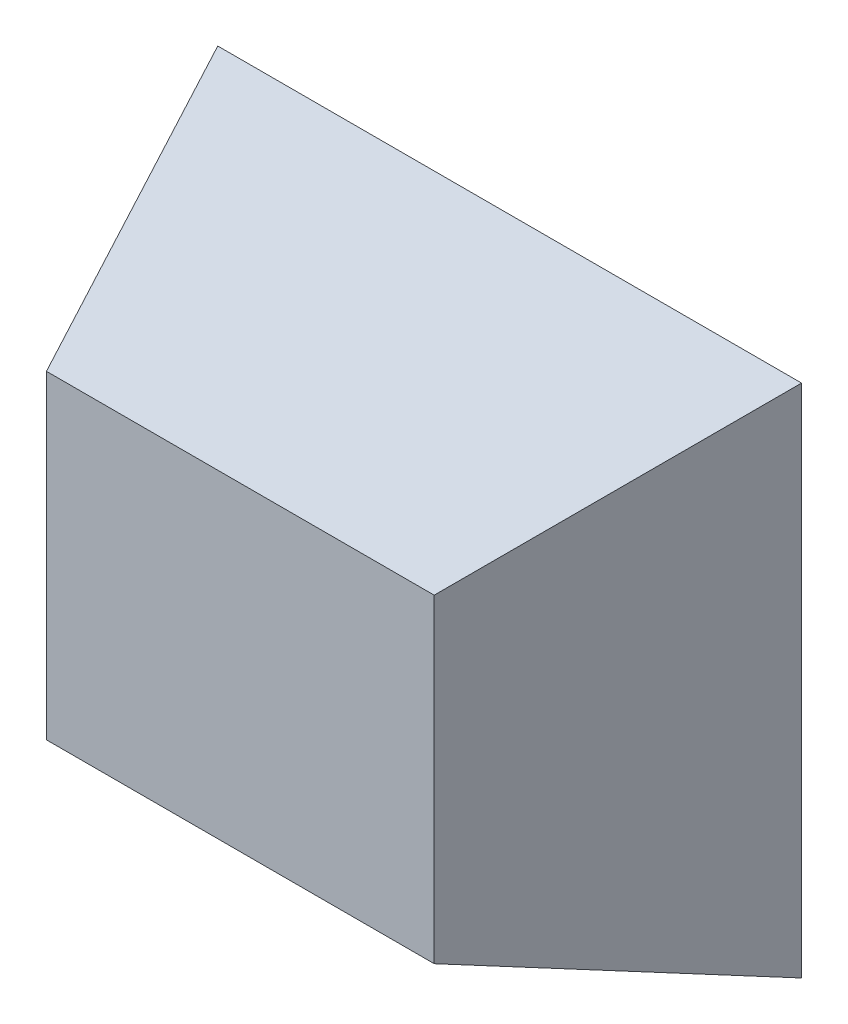
SolidWorks part; units mm, degrees
ref_plane "Спереди" through (0, 0, 0) normal (0, 0, 1) x (1, 0, 0)
ref_plane "Сверху" through (0, 0, 0) normal (0, 1, 0) x (1, 0, 0)
ref_plane "Справа" through (0, 0, 0) normal (1, 0, 0) x (0, 0, -1)
sketch "Эскиз1_fr" plane through (0, 0, 0) normal (0, 0, 1) x (1, 0, 0)
  line L1 (0, 0) -> (43.3507, 0)
  line L2 (0, 0) -> (0, -38.2597)
  line L3 (0, -38.2597) -> (43.3507, -38.2597)
  line L4 (43.3507, 0) -> (43.3507, -38.2597)
extrude "Бобышка-Вытянуть1" add sketch "Эскиз1_fr" along normal blind 20 draft 20
